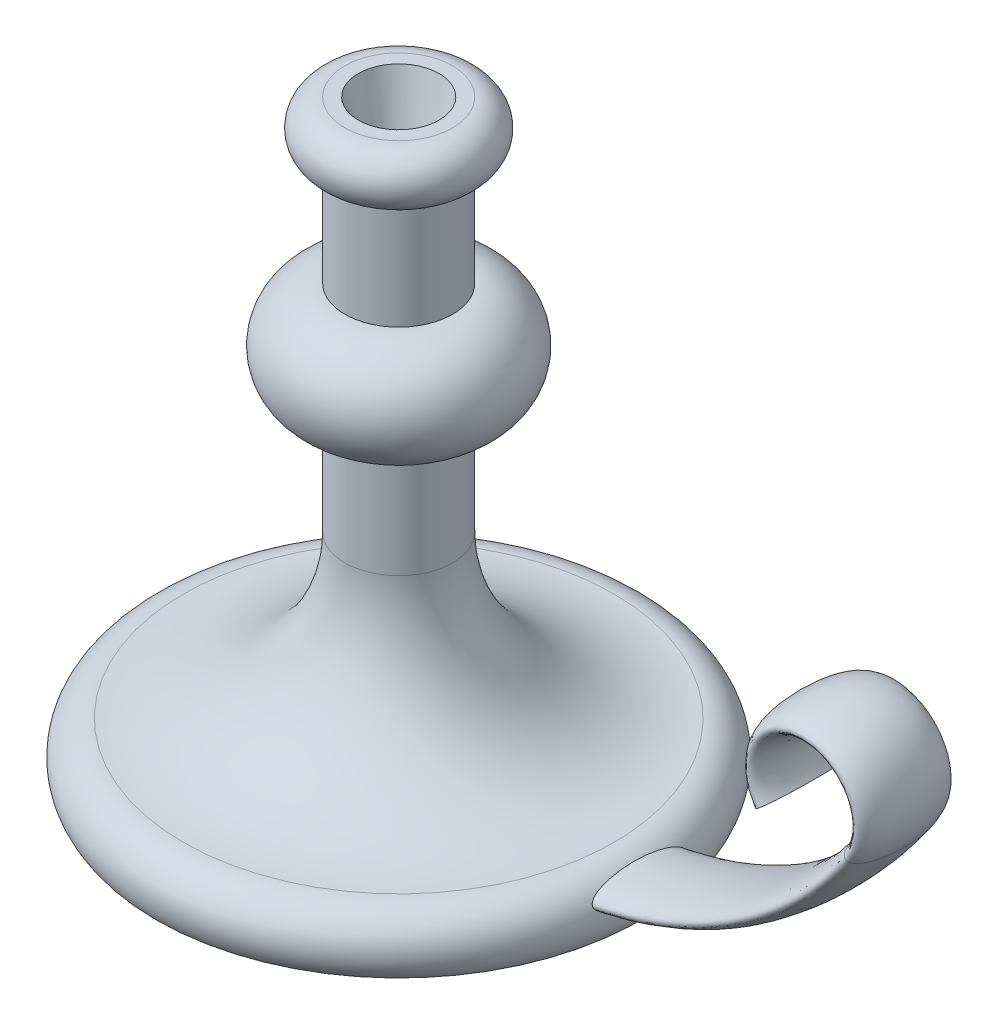
SolidWorks part; units mm, degrees
ref_plane "Front Plane" through (0, 0, 0) normal (0, 0, 1) x (1, 0, 0)
ref_plane "Top Plane" through (0, 0, 0) normal (0, 1, 0) x (1, 0, 0)
ref_plane "Right Plane" through (0, 0, 0) normal (1, 0, 0) x (0, 0, -1)
sketch "Sketch1" plane through (0, 0, 0) normal (0, 0, 1) x (1, 0, 0)
  line L0 (0, 0) -> (0, 220)
  line L1 (20, 220) -> (0, 220)
  line L2 (0, 0) -> (90, 0)
  line L3 (20, 200) -> (20, 160)
  line L4 (20, 120) -> (20, 80)
  arc A0 (20, 220) -> (20, 200) centre (20, 210) cw
  arc A1 (20, 160) -> (20, 120) centre (20, 140) cw
  arc A2 (20, 80) -> (80.0015, 20.0033) centre (79.9967, 80) ccw
  arc A3 (80.0015, 20.0033) -> (90, 0) centre (80.0025, 7.5033) cw
  point P11 (40, 140)
  dimension "D4" = 20
  dimension "D5" = 40
  dimension "D6" = 10
  dimension "D7" = 59.9967
  dimension "D8" = 12.5
  dimension "D1" = 220
  dimension "D2" = 90
  dimension "D3" = 20
revolve "Revolve1" add sketch "Sketch1" angle 360 about L0
sketch "Sketch2" plane through (0, 0, 0) normal (0, 0, 1) x (1, 0, 0)
  line L0 (0, 10) -> (60, 10)
  line L1 (0, 227.4356) -> (0, 175.1288) construction
  line L2 (0, 200) -> (0, 160) construction
  line L3 (-90, 0) -> (90, 0) construction
  arc A0 (60, 10) -> (183.5921, 75) centre (60, 160) ccw
  arc A1 (183.5921, 75) -> (150.6342, 75) centre (167.1131, 86.3333) ccw
  point P13 (30, 10)
  dimension "D2" = 150
  dimension "D4" = 20
  dimension "D5" = 65
  dimension "D3" = 10
  dimension "D1" = 60
sketch "Sketch4" plane through (0, 0, 0) normal (1, 0, 0) x (0, 0, -1)
  ellipse E0 centre (0, 10) end of major axis (17.5, 10) minor radius 5
  dimension "D1" = 10
  dimension "D2" = 35
sweep "Sweep1" add profiles "Sketch4" path "Sketch2"
sketch "Sketch5" plane through (0, 220, 0) normal (0, 1, 0) x (1, 0, 0)
  circle A0 centre (0, 0) radius 15
  dimension "D1" = 30
extrude "Cut-Extrude1" cut sketch "Sketch5" against normal blind 25 draft 15 contours A0
